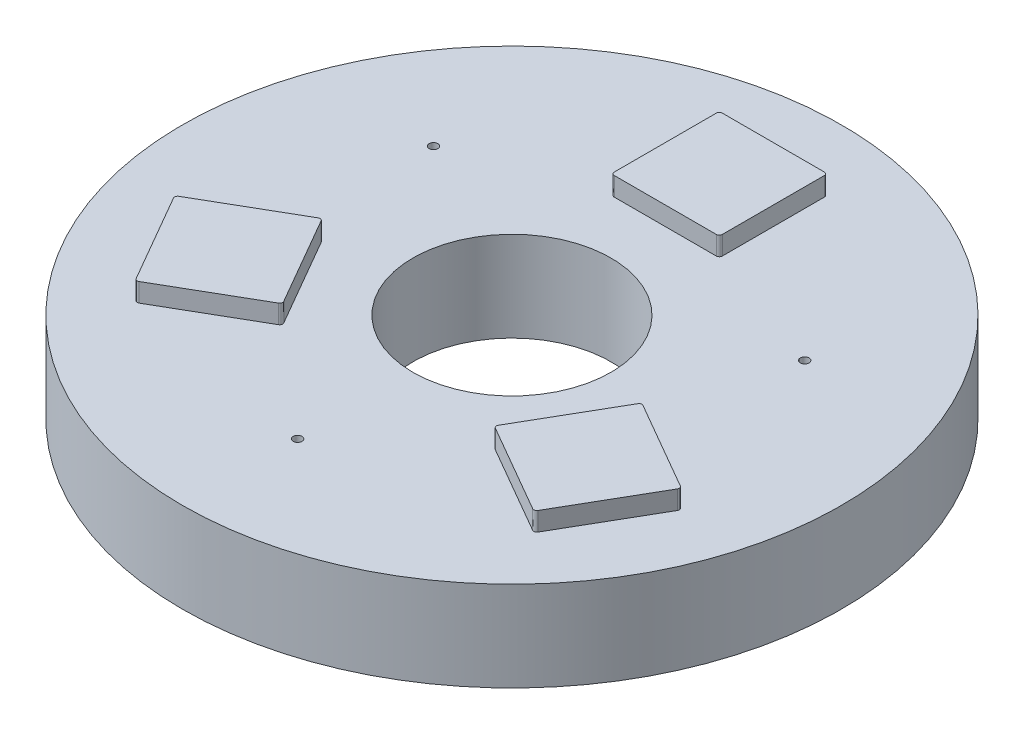
SolidWorks part; units mm, degrees
ref_plane "Front Plane" through (0, 0, 0) normal (0, 0, 1) x (1, 0, 0)
ref_plane "Top Plane" through (0, 0, 0) normal (0, 1, 0) x (1, 0, 0)
ref_plane "Right Plane" through (0, 0, 0) normal (1, 0, 0) x (0, 0, -1)
sketch "Sketch1" plane through (0, 0, 0) normal (0, 1, 0) x (1, 0, 0)
  circle A0 centre (0, 0) radius 18
  dimension "D1" = 36
extrude "Boss-Extrude1" add sketch "Sketch1" along normal mid plane 4.9101
sketch "Sketch3" plane through (0, 0, 0) normal (0, 1, 0) x (1, 0, 0)
  circle A0 centre (0, -11.705) radius 0.2389
  circle A1 centre (0, 0) radius 5.4101
  dimension "D1" = 0.4777
  dimension "D3" = 10.8202
  dimension "D2" = 11.705
extrude "Cut-Extrude1" cut sketch "Sketch3" against normal through all both and the other way through all
pattern_circular "CirPattern1" count 3 over 360 about axis through (0, 0, 0) along (0, 1, 0) of "Cut-Extrude1"
sketch "Sketch5" plane through (0, 2.455, 0) normal (0, 1, 0) x (1, 0, 0)
  line L0 (0, 0) -> (-12.3649, -7.1389) construction
  line L1 (-8.8712, -1.7145) -> (-13.6985, -4.5016)
  line L2 (-8.6476, -1.7744) -> (-5.8605, -6.6018)
  line L3 (-5.9204, -6.8254) -> (-10.7478, -9.6125)
  line L4 (-13.7585, -4.7252) -> (-10.9714, -9.5526)
  line L5 (0, 0) -> (0, -5.0148) construction
  arc A0 (-8.8712, -1.7145) -> (-8.6476, -1.7744) centre (-8.7893, -1.8563) cw
  arc A1 (-5.8605, -6.6018) -> (-5.9204, -6.8254) centre (-6.0022, -6.6837) cw
  arc A2 (-10.7478, -9.6125) -> (-10.9714, -9.5526) centre (-10.8296, -9.4707) cw
  arc A3 (-13.6985, -4.5016) -> (-13.7585, -4.7252) centre (-13.6167, -4.6434) ccw
  point P6 (-8.3341, -8.2189)
  dimension "D1" = 0.1637
  dimension "D3" = 5.9015
  dimension "D2" = 60
  dimension "D4" = 11.705
extrude "Boss-Extrude2" add sketch "Sketch5" along normal blind 1.0229
pattern_circular "CirPattern2" count 3 over 360 about axis through (0, 0, 0) along (0, 1, 0) of "Boss-Extrude2"
mirror "Mirror1" about plane through (0, 0, 0) normal (0, 1, 0) of "CirPattern2", "Boss-Extrude2"
equation "\"D1@Sketch1\"=(\"Upper_Mount_largest_radius\"*2)-1mm"
equation "\"Piston_orifice_dia\"=0.47773"
equation "\"D1@Sketch3\"=\"Piston_orifice_dia\""
equation "\"Upper_Mount_largest_radius\" =18.5"
equation "\"Lower_Mount_piston_rod_radius\"\t=4.9101"
equation "\"D3@Sketch3\"=(\"Lower_Mount_piston_rod_radius\"*2)+1mm"
equation "\"D1@Boss-Extrude1\"=\"Lower_Mount_piston_rod_radius\""
equation "\"D2@Sketch3\"=(((\"Upper_Mount_largest_radius\"-0.5mm)-(\"Lower_Mount_piston_rod_radius\"+0.5mm))/2)+(\"Lower_Mount_piston_rod_radius\"+0.5mm)"
equation "\"D1@Boss-Extrude2\"=\"Lower_Mount_piston_rod_radius\"/4.8"
equation "\"Upper_mount_wall_thickness\" =12"
equation "\"Lower_Mount_piston_rod_length\" =149"
equation "\"Spring_inner_dia\" =80"
equation "\"Spring_wire_dia\" =8"
equation "\"D4@Sketch5\"=(((\"Upper_Mount_largest_radius\"-0.5mm)-(\"Lower_Mount_piston_rod_radius\"+0.5mm))/2)+(\"Lower_Mount_piston_rod_radius\"+0.5mm)"
equation "\"D1@Sketch5\"=\"Lower_Mount_piston_rod_radius\"/30"
equation "\"D3@Sketch5\"=((\"Upper_Mount_largest_radius\"-0.5mm)-(\"Lower_Mount_piston_rod_radius\"+0.5mm))/2.133333333333333333333333"
